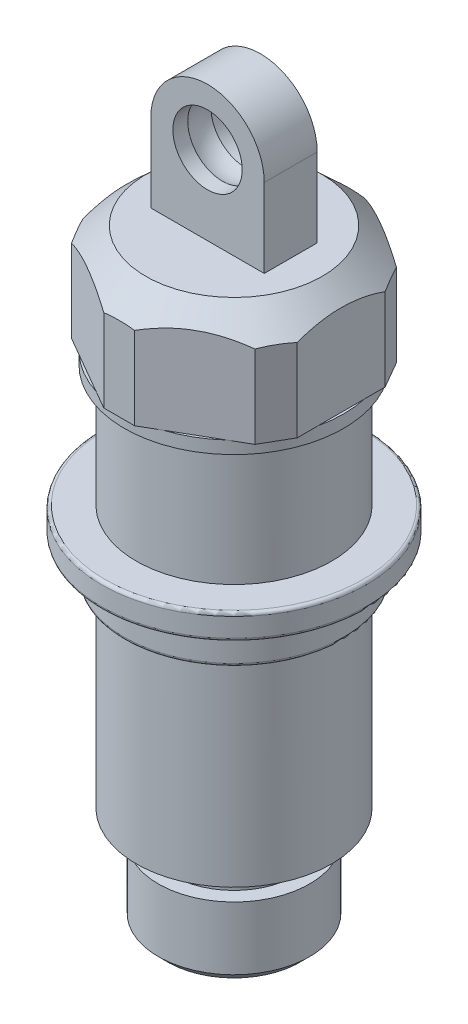
SolidWorks part; units mm, degrees
ref_plane "Front Plane" through (0, 0, 0) normal (0, 0, 1) x (1, 0, 0)
ref_plane "Top Plane" through (0, 0, 0) normal (0, 1, 0) x (1, 0, 0)
ref_plane "Right Plane" through (0, 0, 0) normal (1, 0, 0) x (0, 0, -1)
sketch "Sketch1" plane through (0, 0, 0) normal (0, 0, 1) x (1, 0, 0)
  line L0 (0, 39.4) -> (0, 0) construction
  line L1 (0, 0) -> (6, 0)
  line L2 (6, 0) -> (6, 5.75)
  line L3 (6, 5.75) -> (4.875, 5.75)
  line L4 (4.875, 5.75) -> (4.875, 6.5)
  line L5 (4.875, 6.5) -> (7.75, 8)
  line L6 (7.75, 8) -> (7.75, 38.4)
  line L7 (7.75, 38.4) -> (8.7, 38.4)
  line L8 (8.7, 38.4) -> (8.7, 39.4)
  line L10 (8.7, 39.4) -> (0, 39.4)
  line L12 (0, 39.4) -> (0, 0)
  dimension "D2" = 39.4
  dimension "D3" = 1
  dimension "D4" = 5.75
  dimension "D5" = 0.75
  dimension "D6" = 1.5
  dimension "D7" = 7.75
  dimension "D8" = 6
  dimension "D9" = 4.875
  dimension "D10" = 8.7
revolve "Revolve1" add sketch "Sketch1" angle 360 about L0
sketch "Sketch3" plane through (0, 39.4, 0) normal (0, 1, 0) x (1, 0, 0)
  line L1 (0, 9.815) -> (-8.5, 4.9075)
  line L2 (-8.5, 4.9075) -> (-8.5, -4.9075)
  line L3 (-8.5, -4.9075) -> (0, -9.815)
  line L4 (0, -9.815) -> (8.5, -4.9075)
  line L5 (8.5, -4.9075) -> (8.5, 4.9075)
  line L6 (8.5, 4.9075) -> (0, 9.815)
  circle A0 centre (0, 0) radius 8.5 construction
extrude "Boss-Extrude1" add sketch "Sketch3" along normal blind 8.6
chamfer "Chamfer1" distance 1.414 angle 30 6 edges at (-8.5, 43.7, 4.9075) (-8.5, 43.7, -4.9075) (0, 43.7, -9.815) (8.5, 43.7, -4.9075) (8.5, 43.7, 4.9075) (0, 43.7, 9.815)
sketch "Sketch5" plane through (0, 0, 0) normal (0, 0, 1) x (1, 0, 0)
  line L0 (7.75, 28.802) -> (10.5, 28.802)
  line L1 (7.75, 8) -> (7.75, 38.4) construction
  line L2 (10.5, 28.802) -> (10.5, 26.802)
  line L3 (10.5, 26.802) -> (8.7, 26.802)
  line L4 (8.7, 26.802) -> (8.7, 23.802)
  line L5 (8.7, 23.802) -> (7.75, 23.802)
  line L6 (7.75, 23.802) -> (7.75, 28.802)
  line L7 (-8.7, 38.4) -> (8.7, 38.4) construction
  line L8 (0, 0) -> (0, 33.2479) construction
  dimension "D1" = 9.598
  dimension "D2" = 8.7
  dimension "D3" = 10.5
  dimension "D4" = 5
  dimension "D5" = 3
revolve "Revolve2" add sketch "Sketch5" angle 360 about L8
fillet "Fillet2" radius 0.25 3 edges at (0, 28.802, -10.5) (0, 26.802, -10.5) (0, 23.802, -8.7)
sketch "Sketch6" plane through (0, 0, 0) normal (0, -1, 0) x (1, 0, 0)
  circle A0 centre (0, 0) radius 1.5
  dimension "D1" = 3
extrude "Cut-Extrude1" cut sketch "Sketch6" against normal blind 28
sketch "Sketch7" plane through (0, 0, 0) normal (0, 0, 1) x (1, 0, 0)
  line L0 (0, 48) -> (0, 54.25) construction
  line L1 (-1.2246, 48) -> (1.2246, 48) construction
  line L2 (4.5, 54.25) -> (4.5, 48)
  line L3 (1.2246, 48) -> (7.2754, 48) construction
  line L4 (-4.5, 54.25) -> (-4.5, 48)
  line L5 (-7.2754, 48) -> (-1.2246, 48) construction
  line L6 (-4.5, 48) -> (4.5, 48)
  arc A0 (4.5, 54.25) -> (-4.5, 54.25) centre (0, 54.25) ccw
  dimension "D2" = 9
  dimension "D1" = 6.25
extrude "Boss-Extrude2" add sketch "Sketch7" along normal mid plane 4.2
sketch "Sketch8" plane through (0, 0, 0) normal (0, 0, 1) x (1, 0, 0)
  line L0 (0, 48) -> (0, 57.15) construction
  line L1 (-4.5, 48) -> (4.5, 48) construction
  line L2 (0, 57.15) -> (0, 51.35)
  arc A0 (0, 51.35) -> (0, 57.15) centre (0, 54.25) ccw
  dimension "D1" = 5.8
revolve "Cut-Revolve1" cut sketch "Sketch8" angle 360 about L0
sketch "Sketch10" plane through (0, 0, 0) normal (0, 0, 1) x (1, 0, 0)
  line L0 (7, 48) -> (8.5, 46.6)
  line L1 (1.2246, 48) -> (7.2754, 48) construction
  line L2 (8.5, 48) -> (8.5, 39.4) construction
  line L3 (8.5, 46.6) -> (10.1247, 45.0836)
  line L4 (10.1247, 47.8194) -> (7, 50.7358)
  line L5 (7, 50.7358) -> (7, 48)
  line L6 (-4.5, 48) -> (4.5, 48) construction
  line L7 (0, 0) -> (0, 63.5668) construction
  line L8 (10.1247, 45.0836) -> (10.1247, 47.8194)
  point P6 (0, 48)
  dimension "D1" = 7.2
  dimension "D2" = 7
  dimension "D3" = 2
  dimension "D4" = 2.2224
revolve "Cut-Revolve2" cut sketch "Sketch10" angle 360 about L7
sketch "Sketch9" plane through (0, 0, 2.1) normal (0, 0, 1) x (1, 0, 0)
  circle A0 centre (0, 54.25) radius 2.75
  dimension "D1" = 5.5
extrude "Cut-Extrude2" cut sketch "Sketch9" against normal blind 4.2
chamfer "Chamfer3" distance 0.75 angle 45 1 edges at (-6, 0, 0)
